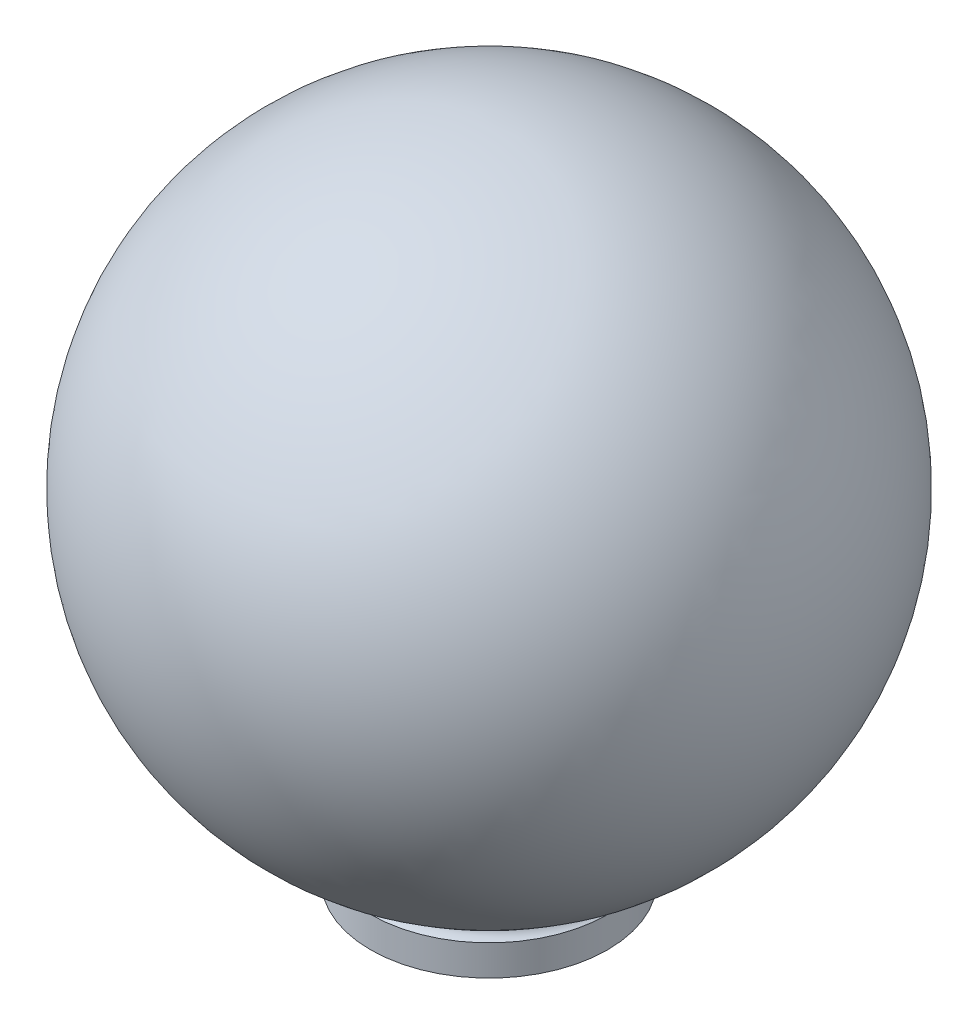
SolidWorks part; units mm, degrees
material "Acrylic (Medium-high impact)"
ref_plane "Front Plane" through (0, 0, 0) normal (0, 0, 1) x (1, 0, 0)
ref_plane "Top Plane" through (0, 0, 0) normal (0, 1, 0) x (1, 0, 0)
ref_plane "Right Plane" through (0, 0, 0) normal (1, 0, 0) x (0, 0, -1)
sketch "Sketch1" plane through (0, 0, 0) normal (0, 0, 1) x (1, 0, 0)
  line L0 (0, 0) -> (0, 215.0105) construction
  line L2 (43.942, 0) -> (43.942, 19.96)
  line L5 (48.133, 0) -> (48.133, 12.4072)
  line L6 (43.942, 0) -> (48.133, 0)
  line L7 (46.482, 19.96) -> (8.255, 19.96) construction
  line L8 (-48.133, 0) -> (-48.133, 12.4072) construction
  line L9 (-43.942, 0) -> (-48.133, 0) construction
  line L10 (-43.942, 0) -> (-43.942, 19.96) construction
  line L11 (0, 265.1481) -> (0, 264.2406)
  arc A1 (48.133, 12.4072) -> (46.482, 19.96) centre (50.9075, 16.9706) cw
  arc A2 (-48.133, 12.4072) -> (-46.482, 19.96) centre (-50.9075, 16.9706) ccw construction
  circle A4 centre (0, 138.1481) radius 127 construction
  arc A7 (46.482, 19.96) -> (0, 265.1481) centre (0, 138.1481) ccw
  arc A8 (43.942, 19.96) -> (0, 264.2406) centre (0, 138.1481) ccw
  dimension "D6" = 4.191
  dimension "D5" = 6.9655
  dimension "D8" = 5.3406
  dimension "D10" = 254
  dimension "D2" = 43.942
  dimension "D3" = 19.96
  dimension "D4" = 12.4072
  dimension "D7" = 2.54
revolve "Revolve1" add sketch "Sketch1" angle 360 about L0
